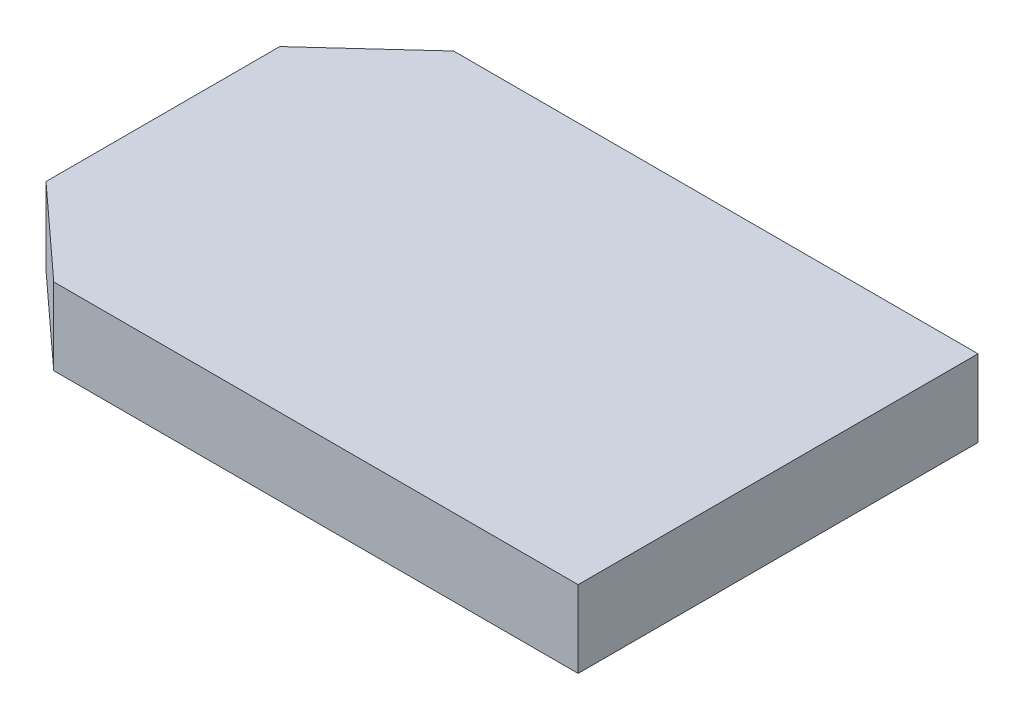
SolidWorks part; units mm, degrees
ref_plane "Front Plane" through (0, 0, 0) normal (0, 0, 1) x (1, 0, 0)
ref_plane "Top Plane" through (0, 0, 0) normal (0, 1, 0) x (1, 0, 0)
ref_plane "Right Plane" through (0, 0, 0) normal (1, 0, 0) x (0, 0, -1)
sketch "Sketch1" plane through (0, 0, 0) normal (0, 1, 0) x (1, 0, 0)
  line L0 (-1000, 0) -> (49000, 0) construction
  line L1 (-127, -48.26) -> (-127, 48.26)
  line L2 (-127, 48.26) -> (-89.5189, 82.55)
  line L3 (-89.5189, 82.55) -> (127, 82.55)
  line L4 (127, 82.55) -> (127, -82.55)
  line L5 (-89.5189, -82.55) -> (127, -82.55)
  line L6 (-127, -48.26) -> (-89.5189, -82.55)
  point P9 (127, 0)
  point P11 (-127, 0)
  dimension "D1" = 82.55
  dimension "D2" = 50.8
  dimension "D3" = 48.26
  dimension "D4" = 254
  dimension "D5" = 127
extrude "Boss-Extrude1" add sketch "Sketch1" along normal blind 31.75
